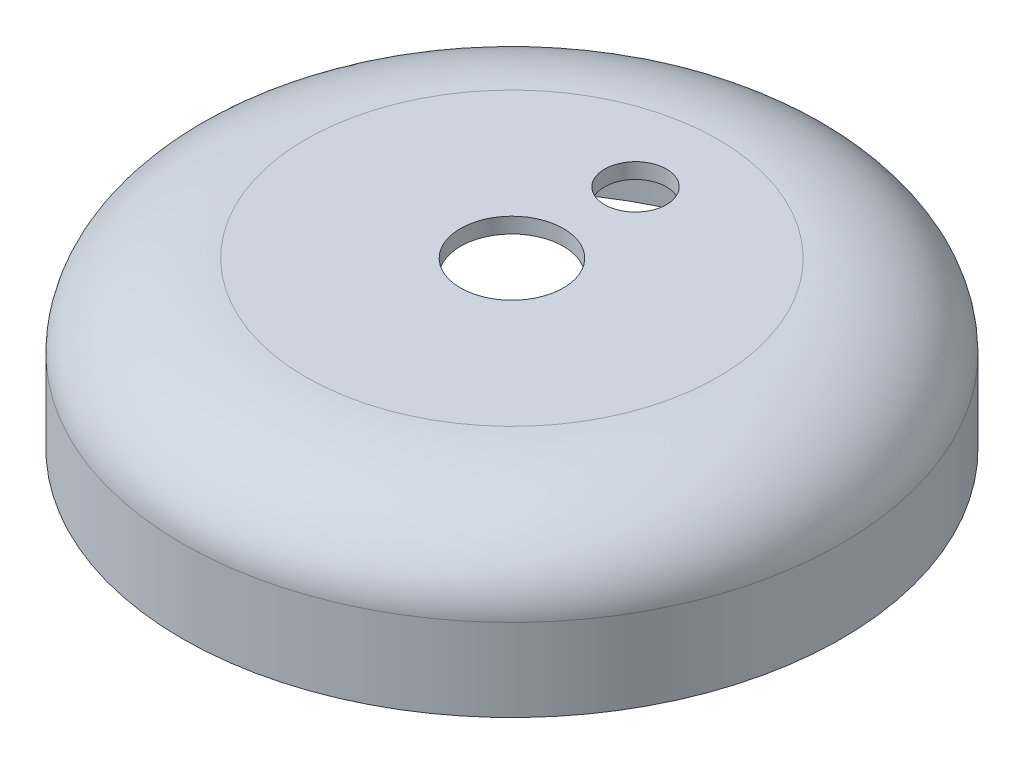
SolidWorks part; units mm, degrees
material "6061-T6 (SS)"
ref_plane "Front" through (0, 0, 0) normal (0, 0, 1) x (1, 0, 0)
ref_plane "Top" through (0, 0, 0) normal (0, 1, 0) x (1, 0, 0)
ref_plane "Right" through (0, 0, 0) normal (1, 0, 0) x (0, 0, -1)
sketch "Sketch1" plane through (0, 0, 0) normal (0, 0, 1) x (1, 0, 0)
  line L0 (0, 0) -> (101.6, 0) construction
  line L1 (101.6, 0) -> (101.6, -67.9188) construction
  line L2 (0, 29.5111) -> (0, -26.7187) construction
  line L3 (0, 0) -> (0, -4.7625)
  line L4 (0, 0) -> (63.5, 0)
  line L5 (0, -4.7625) -> (63.5, -4.7625)
  line L6 (101.6, 5.9654) -> (96.8375, 5.9654) construction
  line L7 (96.8375, 5.9654) -> (96.8375, -58.8285) construction
  line L9 (63.5, -25.4) -> (127.5739, -25.4) construction
  line L12 (63.5, 0) -> (63.5, -38.8167) construction
  line L14 (96.8375, -50.8) -> (101.6, -50.8)
  line L15 (101.6, -50.8) -> (101.6, -25.4)
  line L16 (96.8375, -50.8) -> (96.8375, -25.4)
  ellipse E0 centre (63.5, -25.4) end of major axis (96.8375, -25.4) minor radius 20.6375 (96.8375, -25.4) -> (63.5, -4.7625) ccw
  ellipse E1 centre (63.5, -25.4) end of major axis (25.4, -25.4) minor radius 25.4 (63.5, 0) -> (101.6, -25.4) cw
  dimension "D1" = 101.6
  dimension "D2" = 63.5
  dimension "D3" = 25.4
  dimension "D4" = 4.7625
  dimension "D5" = 4.7625
  dimension "D6" = 25.4
revolve "Revolve1" add sketch "Sketch1" angle 360 about L2
sketch "Sketch2" plane through (0, 0, 0) normal (0, 1, 0) x (1, 0, 0)
  line L0 (0, 0) -> (0, 199.7485) construction
  line L1 (0, 0) -> (303.3008, 0) construction
  circle A0 centre (0, 38.1) radius 9.525
  circle A1 centre (0, 0) radius 15.875
  dimension "D1" = 19.05
  dimension "D3" = 31.75
  dimension "D2" = 38.1
extrude "Cut-Extrude1" cut sketch "Sketch2" against normal blind 25.4
